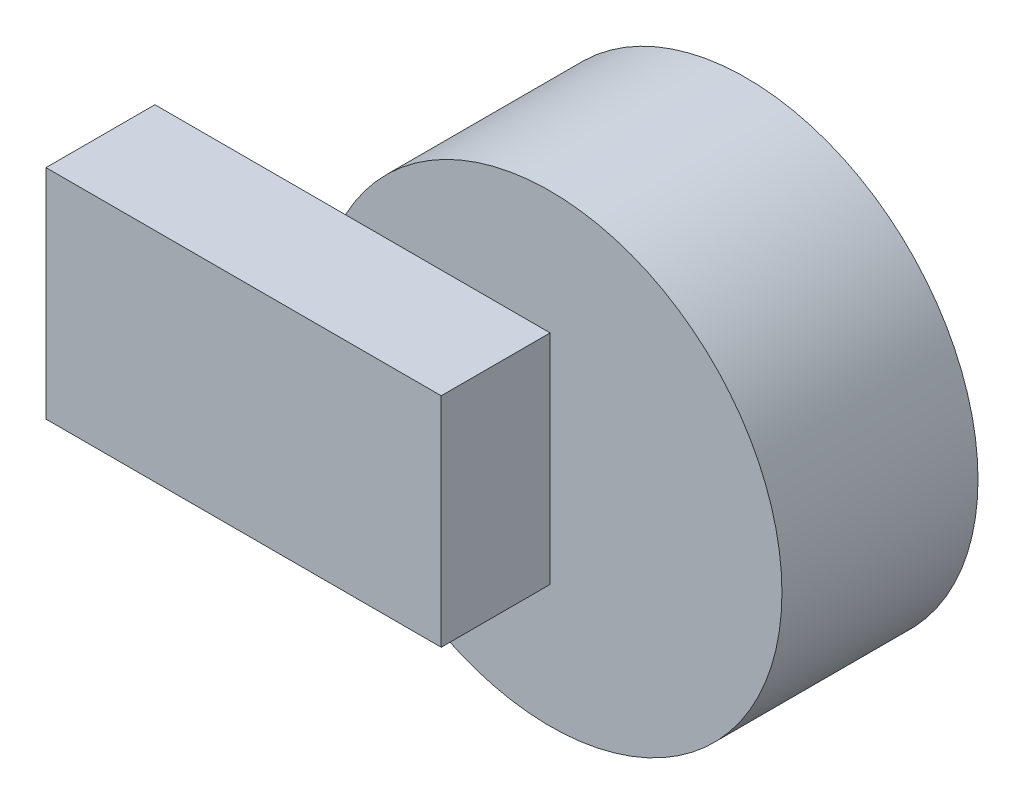
SolidWorks part; units mm, degrees
ref_plane "Front" through (0, 0, 0) normal (0, 0, 1) x (1, 0, 0)
ref_plane "Top" through (0, 0, 0) normal (0, 1, 0) x (1, 0, 0)
ref_plane "Right" through (0, 0, 0) normal (1, 0, 0) x (0, 0, -1)
sketch "Sketch3" plane through (0, 0, 0) normal (0, 0, 1) x (1, 0, 0)
  circle A0 centre (0, 0) radius 42.57
  dimension "D1" = 85.14
extrude "Boss-Extrude1" add sketch "Sketch3" along normal blind 36
sketch "Sketch4" plane through (0, 0, 36) normal (0, 0, 1) x (1, 0, 0)
  line L0 (0, 0) -> (0, 20)
  line L1 (0, 20) -> (0, -20)
  line L2 (0, 20) -> (-72.57, 20)
  line L3 (-72.57, 20) -> (-72.57, -20)
  line L4 (-72.57, -20) -> (0, -20)
  line L5 (-42.57, 0) -> (-42.57, 20)
  line L6 (-42.57, 20) -> (-42.57, -20)
  circle A0 centre (0, 0) radius 42.57 construction
  circle M5 centre (0, 0) radius 42.57
  dimension "D1" = 20
  dimension "D2" = 20
  dimension "D3" = 30
extrude "Boss-Extrude2" add sketch "Sketch4" along normal blind 20 contours L5 L2 M5 | L4 L1 L0 L2 M5 | L6 L5 L2 L3 L4 | L6 L4 M5
